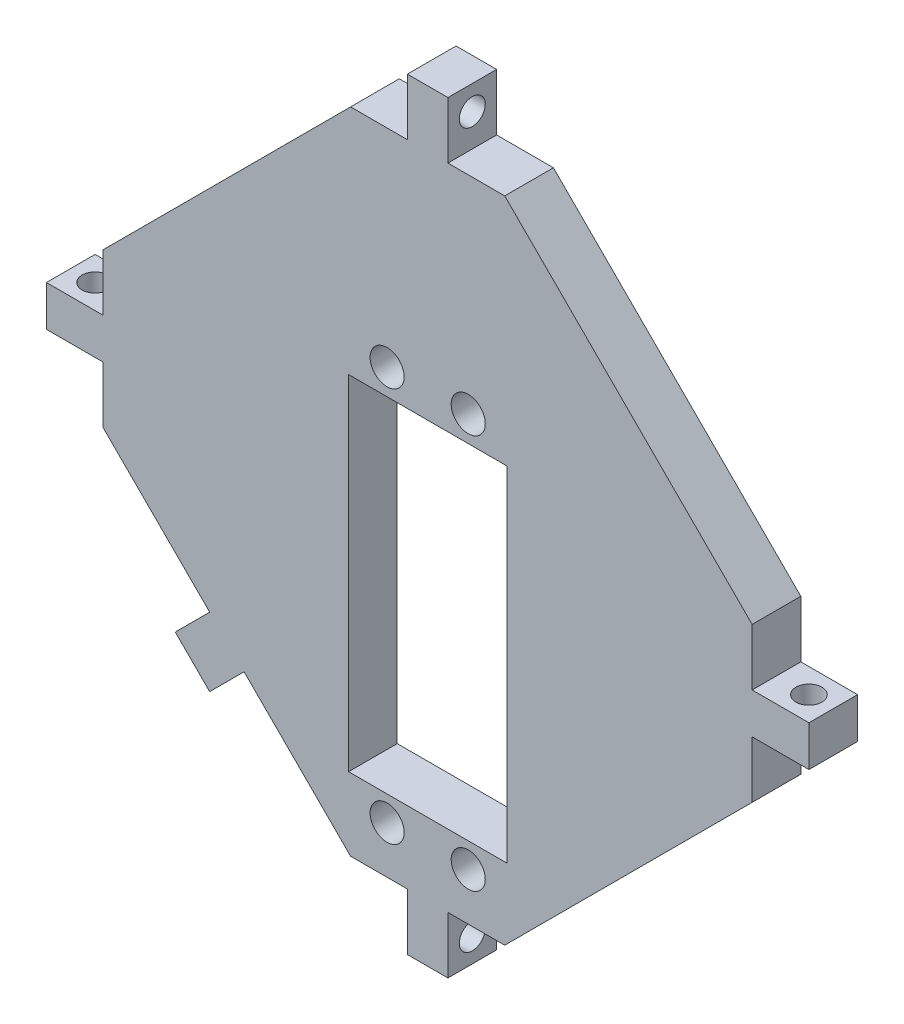
SolidWorks part; units mm, degrees
ref_plane "前视基准面" through (0, 0, 0) normal (0, 0, 1) x (1, 0, 0)
ref_plane "上视基准面" through (0, 0, 0) normal (0, 1, 0) x (1, 0, 0)
ref_plane "右视基准面" through (0, 0, 0) normal (1, 0, 0) x (0, 0, -1)
sketch "草图1" plane through (0, 0, 0) normal (0, 0, 1) x (1, 0, 0)
  line L0 (-49.4975, 0) -> (49.4975, 0) construction
  line L1 (-49.4975, 0) -> (0, 49.4975)
  line L2 (-49.4975, 0) -> (0, -49.4975)
  line L3 (0, -49.4975) -> (49.4975, 0)
  line L4 (0, 49.4975) -> (49.4975, 0)
  line L5 (0, 49.4975) -> (0, -49.4975) construction
  line L6 (-9.5, -39.9975) -> (9.5, -39.9975)
  line L7 (-9.75, 10.3) -> (9.75, 10.3)
  line L8 (-9.75, 10.3) -> (-9.75, -30.1)
  line L9 (-9.75, -30.1) -> (9.75, -30.1)
  line L10 (9.75, 10.3) -> (9.75, -30.1)
  line L11 (-5, 14.465) -> (5, 14.465) construction
  line L12 (-5, 14.465) -> (-5, -34.165) construction
  line L13 (-5, -34.165) -> (5, -34.165) construction
  line L14 (5, 14.465) -> (5, -34.165) construction
  line L15 (-9.75, -30.1) -> (9.75, -30.1)
  line L16 (-9.75, -30.1) -> (-9.75, -36.85)
  line L17 (-9.75, -36.85) -> (9.75, -36.85)
  line L18 (9.75, -30.1) -> (9.75, -36.85)
  line L19 (-2.5, -39.9975) -> (-2.5, -46.9975)
  line L20 (-2.5, -46.9975) -> (2.5, -46.9975)
  line L21 (2.5, -46.9975) -> (2.5, -39.9975)
  line L22 (-39.9975, 9.5) -> (-39.9975, -9.5)
  line L23 (-39.9975, 2.5) -> (-46.9975, 2.5)
  line L24 (-46.9975, 2.5) -> (-46.9975, -2.5)
  line L25 (-46.9975, -2.5) -> (-39.9975, -2.5)
  line L26 (9.5, 39.9975) -> (-9.5, 39.9975)
  line L27 (2.5, 39.9975) -> (2.5, 46.9975)
  line L28 (2.5, 46.9975) -> (-2.5, 46.9975)
  line L29 (-2.5, 46.9975) -> (-2.5, 39.9975)
  line L30 (39.9975, -9.5) -> (39.9975, 9.5)
  line L31 (39.9975, -2.5) -> (46.9975, -2.5)
  line L32 (46.9975, -2.5) -> (46.9975, 2.5)
  line L33 (46.9975, 2.5) -> (39.9975, 2.5)
  circle A0 centre (-5, 14.465) radius 2.1
  circle A1 centre (5, 14.465) radius 2.1
  circle A2 centre (-5, -34.165) radius 2.1
  circle A3 centre (5, -34.165) radius 2.1
  point P19 (0, 0)
  point P25 (0, -46.9975)
  point P49 (0, 0)
  point P288 (0, 0)
  dimension "D7" = 36.85
  dimension "D5" = 70
  dimension "D1" = 19.5
  dimension "D2" = 40.4
  dimension "D3" = 10
  dimension "D4" = 48.63
  dimension "D6" = 4.165
  dimension "D9" = 5
  dimension "D10" = 7
  dimension "D8" = 4
extrude "凸台-拉伸2" add sketch "草图1" along normal blind 6 contours L3 L30 L4 L26 L1 L22 L2 L6 A1 A0 L10 L18 L17 L16 L8 L7 | L28 L29 L26 L27 | L24 L25 L22 L23 | L20 L21 L6 L19 | L32 L33 L30 L31 | L18 L9 L16 L17 A3 A2
sketch "草图2" plane through (0, -2.5, 0) normal (0, -1, 0) x (1, 0, 0)
  line L1 (-46.9975, 6) -> (-40.9975, 6)
  line L2 (-46.9975, 6) -> (-46.9975, 0)
  line L3 (-46.9975, 0) -> (-40.9975, 0)
  line L4 (-40.9975, 6) -> (-40.9975, 0)
  line L5 (-43.9975, 0) -> (-43.9975, 6) construction
  line L6 (-46.9975, 3) -> (-40.9975, 3) construction
  circle A0 centre (-43.9975, 3) radius 1.6
  point P556 (-43.9975, 3)
extrude "切除-拉伸1" cut sketch "草图2" against normal blind 5 contours A0
sketch "草图3" plane through (2.5, 0, 0) normal (1, 0, 0) x (0, 0, -1)
  line L0 (-6, -46.9975) -> (-6, -39.9975) construction
  line L1 (0, -46.9975) -> (-6, -46.9975)
  line L2 (0, -46.9975) -> (0, -40.9975)
  line L3 (0, -40.9975) -> (-6, -40.9975)
  line L4 (-6, -46.9975) -> (-6, -40.9975)
  line L5 (-3, -40.9975) -> (-3, -46.9975) construction
  line L6 (0, -43.9975) -> (-6, -43.9975) construction
  circle A0 centre (-3, -43.9975) radius 1.6
  point P368 (-3, -43.9975)
extrude "切除-拉伸2" cut sketch "草图3" against normal blind 5 contours A0
sketch "草图4" plane through (0, 2.5, 0) normal (0, 1, 0) x (1, 0, 0)
  line L0 (46.9975, -6) -> (39.9975, -6) construction
  line L1 (46.9975, 0) -> (40.9975, 0)
  line L2 (46.9975, 0) -> (46.9975, -6)
  line L3 (46.9975, -6) -> (40.9975, -6)
  line L4 (40.9975, 0) -> (40.9975, -6)
  line L5 (43.9975, -6) -> (43.9975, 0) construction
  line L6 (46.9975, -3) -> (40.9975, -3) construction
  circle A0 centre (43.9975, -3) radius 1.6
  point P136 (43.9975, -3)
extrude "切除-拉伸3" cut sketch "草图4" against normal blind 5 contours A0
sketch "草图5" plane through (-2.5, 0, 0) normal (-1, 0, 0) x (0, 0, 1)
  line L0 (6, 46.9975) -> (6, 39.9975) construction
  line L1 (0, 46.9975) -> (6, 46.9975)
  line L2 (0, 46.9975) -> (0, 40.9975)
  line L3 (0, 40.9975) -> (6, 40.9975)
  line L4 (6, 46.9975) -> (6, 40.9975)
  line L5 (3, 40.9975) -> (3, 46.9975) construction
  line L6 (0, 43.9975) -> (6, 43.9975) construction
  circle A0 centre (3, 43.9975) radius 1.6
  point P192 (3, 43.9975)
extrude "切除-拉伸4" cut sketch "草图5" against normal blind 5 contours A0
sketch "草图6" plane through (0, 0, 6) normal (0, 0, 1) x (1, 0, 0)
  line L0 (-9.5, -39.9975) -> (-39.9975, -9.5)
  line L1 (-9.5, 39.9975) -> (-39.9975, 9.5)
  line L2 (-24.7487, 24.7487) -> (-28.9914, 28.9914) construction
  line L3 (-26.8701, 31.1127) -> (-31.1127, 26.8701)
  line L4 (-31.1127, 26.8701) -> (-26.8701, 22.6274)
  line L5 (-26.8701, 31.1127) -> (-22.6274, 26.8701)
  line L6 (-22.6274, -26.8701) -> (-26.8701, -31.1127)
  line L7 (-26.8701, -31.1127) -> (-31.1127, -26.8701)
  line L8 (-31.1127, -26.8701) -> (-26.8701, -22.6274)
  line L9 (-24.7487, -24.7487) -> (-28.9914, -28.9914) construction
  point P9 (-28.9914, 28.9914)
  dimension "D1" = 6
  dimension "D2" = 6
extrude "凸台-拉伸3" add sketch "草图6" against normal blind 6 contours L8 L7 L6 L0
sketch "草图7" plane through (-2.1213, 2.1213, 0) normal (-0.7071, 0.7071, 0) x (0, 0, 1)
  line L1 (6, -41) -> (0, -41)
  line L2 (6, -41) -> (6, -35)
  line L3 (6, -35) -> (0, -35)
  line L4 (0, -41) -> (0, -35)
  line L5 (3, -35) -> (3, -41) construction
  line L6 (6, -38) -> (0, -38) construction
  circle A0 centre (3, -38) radius 1.6
  point P228 (3, -38)
extrude "切除-拉伸5" cut sketch "草图7" against normal blind 10 contours A0
sketch "草图8" plane through (0, 0, 0) normal (0, 0, -1) x (-1, 0, 0)
  line L1 (-9.75, 10.3) -> (9.75, 10.3) construction
  line L2 (-9.75, 10.3) -> (-9.75, -30.1)
  line L3 (-9.75, -30.1) -> (9.75, -30.1) construction
  line L4 (9.75, 10.3) -> (9.75, -30.1)
  line L5 (-9.75, 11.3) -> (9.75, 11.3)
  line L6 (-9.75, 11.3) -> (-9.75, -31.1)
  line L7 (-9.75, -31.1) -> (9.75, -31.1)
  line L8 (9.75, 11.3) -> (9.75, -31.1)
  line M6 (-9.75, -30.1) -> (-9.75, 10.3)
  line M7 (-9.75, 10.3) -> (9.75, 10.3)
  line M8 (9.75, 10.3) -> (9.75, -30.1)
  line M9 (9.75, -30.1) -> (-9.75, -30.1)
  dimension "D1" = 1
  dimension "D2" = 1
extrude "切除-拉伸6" cut sketch "草图8" against normal blind 10 contours M6 M9 M8 M7 | L8 L5 L6 M7 | L8 L6 L7 M9
